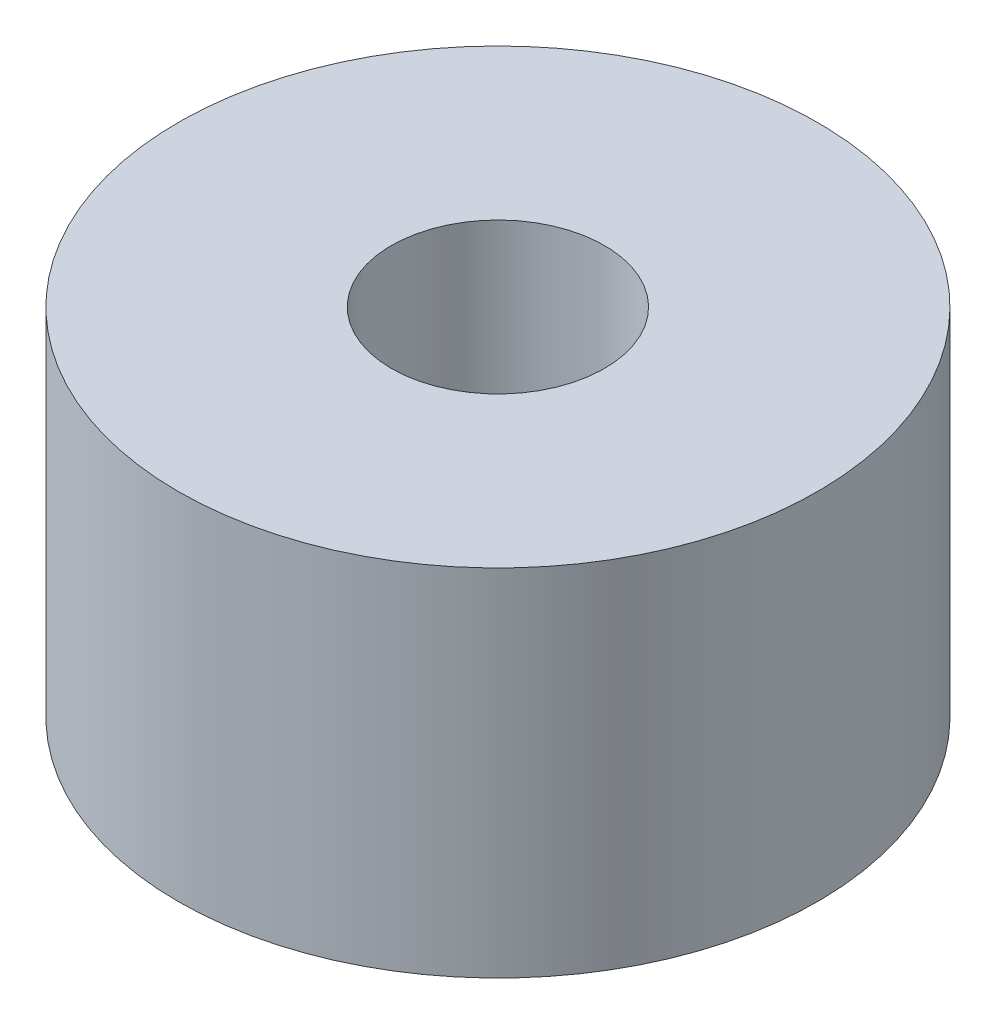
SolidWorks part; units mm, degrees
ref_plane "Front Plane" through (0, 0, 0) normal (0, 0, 1) x (1, 0, 0)
ref_plane "Top Plane" through (0, 0, 0) normal (0, 1, 0) x (1, 0, 0)
ref_plane "Right Plane" through (0, 0, 0) normal (1, 0, 0) x (0, 0, -1)
sketch "Sketch1" plane through (0, 0, 0) normal (0, 1, 0) x (1, 0, 0)
  circle A0 centre (0, 0) radius 4.5
  circle A1 centre (0, 0) radius 1.5
  dimension "D1" = 3
  dimension "D2" = 9
extrude "Body" add sketch "Sketch1" along normal blind 5
